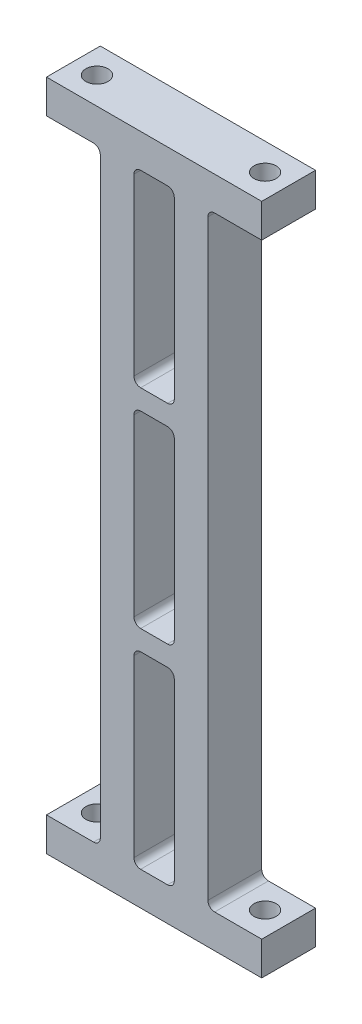
SolidWorks part; units mm, degrees
material "6061 合金"
ref_plane "前视基准面" through (0, 0, 0) normal (0, 0, 1) x (1, 0, 0)
ref_plane "上视基准面" through (0, 0, 0) normal (0, 1, 0) x (1, 0, 0)
ref_plane "右视基准面" through (0, 0, 0) normal (1, 0, 0) x (0, 0, -1)
sketch "草图1" plane through (0, 0, 0) normal (0, 0, 1) x (1, 0, 0)
  line L0 (-16, -45) -> (-16, -50)
  line L1 (-16, 50) -> (16, 50)
  line L2 (-16, 50) -> (-16, 45)
  line L3 (-16, -50) -> (16, -50)
  line L4 (16, 50) -> (16, 45)
  line L5 (-16, 50) -> (16, -50) construction
  line L6 (-16, -50) -> (16, 50) construction
  line L7 (-16, 45) -> (-8, 45)
  line L8 (-16, 45) -> (-16, 50)
  line L9 (-16, 50) -> (16, 50)
  line L10 (16, 45) -> (16, 50)
  line L11 (-16, 45) -> (16, 50) construction
  line L12 (-16, 50) -> (16, 45) construction
  line L13 (-16, -45) -> (-8, -45)
  line L14 (-16, -45) -> (-16, -50)
  line L15 (-16, -50) -> (16, -50)
  line L16 (16, -45) -> (16, -50)
  line L17 (-16, -45) -> (16, -50) construction
  line L18 (-16, -50) -> (16, -45) construction
  line L19 (8, -45) -> (16, -45)
  line L20 (-8, 45) -> (-8, -45)
  line L21 (8, 45) -> (16, 45)
  line L22 (8, 45) -> (8, -45)
  line L23 (-8, 45) -> (8, -45) construction
  line L24 (-8, -45) -> (8, 45) construction
  line L25 (16, -45) -> (16, -50)
  point P0 (0, 0)
  point P6 (0, 47.5)
  point P7 (0, -47.5)
  point P10 (0, 0)
  dimension "D1" = 100
  dimension "D2" = 32
  dimension "D3" = 16
  dimension "D4" = 5
extrude "凸台-拉伸1" add sketch "草图1" along normal blind 8 contours L22 L21 L4 L1 L2 L7 L20 L13 L0 L3 L16 L19
sketch "草图2" plane through (0, -50, 0) normal (0, -1, 0) x (1, 0, 0)
  line L0 (0, 0) -> (0, 8) construction
  line L1 (-16, 8) -> (16, 8) construction
  line L2 (-12.5, 4) -> (12.5, 4)
  circle A0 centre (-12.5, 4) radius 2.1
  circle A1 centre (12.5, 4) radius 2.1
  point P8 (0, 4)
  dimension "D2" = 4.2
  dimension "D3" = 4.2
  dimension "D1" = 25
fillet "圆角1" radius 1 4 edges at (-8, -45, 4) (8, -45, 4) (8, 45, 4) (-8, 45, 4)
sketch "草图3" plane through (0, 0, 8) normal (0, 0, 1) x (1, 0, 0)
  line L0 (-8, 44) -> (-8, -44) construction
  line L1 (-3, -45) -> (3, -45)
  line L2 (-3, -45) -> (-3, 45)
  line L3 (-3, 45) -> (3, 45)
  line L4 (3, -45) -> (3, 45)
  line L5 (-3, -45) -> (3, 45) construction
  line L6 (-3, 45) -> (3, -45) construction
  line L7 (-16, 45) -> (-9, 45) construction
  point P0 (0, 0)
  dimension "D1" = 5
  dimension "D2" = 0
extrude "切除-拉伸2" cut sketch "草图3" against normal blind 10
fillet "圆角2" radius 1 4 edges at (3, -45, 4) (-3, -45, 4) (3, 45, 4) (-3, 45, 4)
hole_wizard "M4 螺纹孔的螺纹孔钻头1" positions "草图4" profile "草图5" hole size "M4" standard "ISO" end condition through all
sketch "草图4" plane through (0, -50, 0) normal (0, -1, 0) x (-1, 0, 0)
  point P0 (-12.5, -4)
  point P3 (12.5, -4)
sketch "草图5" plane through (12.5, -50, 4) normal (1, 0, 0) x (0, 0, -1)
  line L0 (0, 0) -> (0, 100)
  line L1 (0, 100) -> (1.65, 100)
  line L2 (1.65, 100) -> (1.65, 0)
  line L5 (1.65, 0) -> (0, 0)
  line L11 (0, -6.35) -> (0, 107.95) construction
  dimension "通孔孔直径" = 3.3
  dimension "通孔孔深度" = 100
sketch "草图6" plane through (0, 0, 0) normal (0, 0, -1) x (-1, 0, 0)
  line L0 (0, 50) -> (0, -50) construction
  line L1 (16, 50) -> (-16, 50) construction
  line L2 (-1000, 0) -> (49000, 0) construction
  line L3 (3, 44) -> (3, -44) construction
  line L4 (3, 17) -> (-3, 17)
  line L5 (3, 17) -> (3, 14)
  line L6 (3, 14) -> (-3, 14)
  line L7 (-3, 17) -> (-3, 14)
  line L8 (-3, -44) -> (-3, 44) construction
  line L10 (3, -14) -> (-3, -14)
  line L11 (3, -14) -> (3, -17)
  line L12 (3, -17) -> (-3, -17)
  line L13 (-3, -14) -> (-3, -17)
  dimension "D1" = 3
  dimension "D2" = 3
  dimension "D3" = 14
  dimension "D4" = 28
extrude "凸台-拉伸2" add sketch "草图6" against normal up to surface (8 mm away) up to face at (0, 0, 8)
fillet "圆角3" radius 1 8 edges at (3, -14, 4) (3, 17, 4) (-3, 17, 4) (-3, -14, 4) (-3, 14, 4) (3, 14, 4) (3, -17, 4) (-3, -17, 4)
